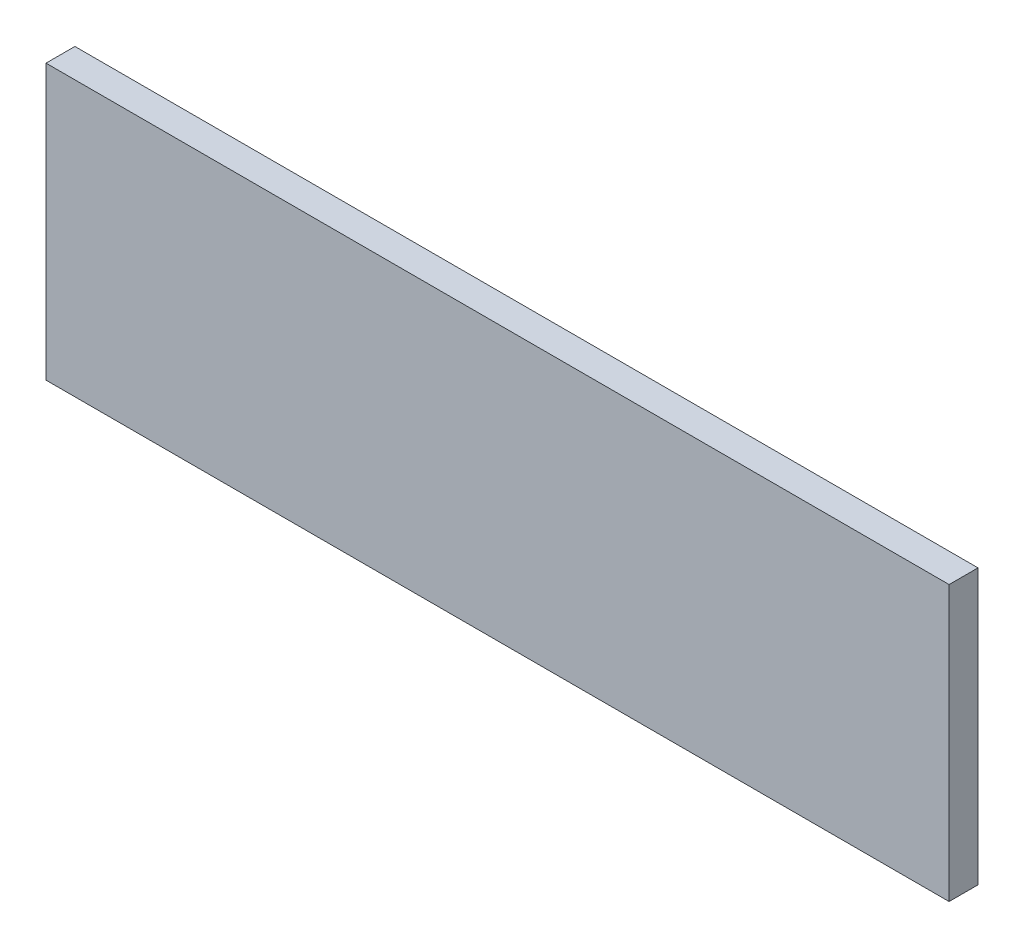
SolidWorks part; units mm, degrees
material "Balsa"
ref_plane "Front Plane" through (0, 0, 0) normal (0, 0, 1) x (1, 0, 0)
ref_plane "Top Plane" through (0, 0, 0) normal (0, 1, 0) x (1, 0, 0)
ref_plane "Right Plane" through (0, 0, 0) normal (1, 0, 0) x (0, 0, -1)
sketch "Sketch1" plane through (0, 0, 0) normal (0, 0, 1) x (1, 0, 0)
  line L0 (-125, 38) -> (125, -38) construction
  line L1 (-125, -38) -> (125, -38)
  line L2 (-125, -38) -> (-125, 38)
  line L3 (-125, 38) -> (125, 38)
  line L4 (125, -38) -> (125, 38)
  line L5 (125, 38) -> (-125, -38) construction
  point P4 (0, 0)
  point P5 (0, 0)
  dimension "D1" = 250
  dimension "D2" = 76
extrude "Boss-Extrude1" add sketch "Sketch1" along normal blind 8
